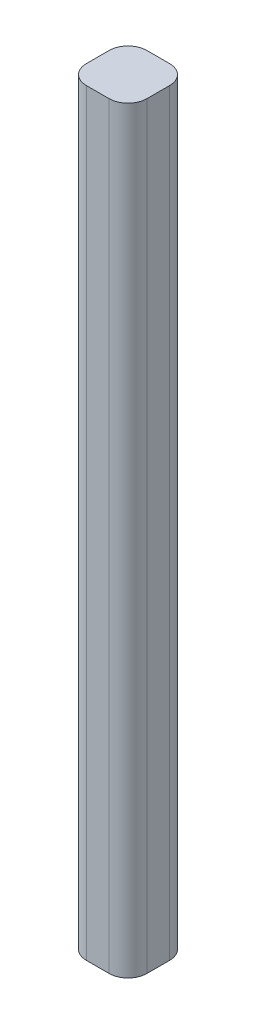
SolidWorks part; units mm, degrees
ref_plane "Front Plane" through (0, 0, 0) normal (0, 0, 1) x (1, 0, 0)
ref_plane "Top Plane" through (0, 0, 0) normal (0, 1, 0) x (1, 0, 0)
ref_plane "Right Plane" through (0, 0, 0) normal (1, 0, 0) x (0, 0, -1)
sketch "Sketch1" plane through (0, 0, 0) normal (0, 1, 0) x (1, 0, 0)
  line L1 (15, -40) -> (-15, -40)
  line L2 (40, -15) -> (40, 15)
  line L3 (15, 40) -> (-15, 40)
  line L4 (-40, -15) -> (-40, 15)
  line L5 (40, -40) -> (-40, 40) construction
  line L6 (40, 40) -> (-40, -40) construction
  circle A0 centre (0, 0) radius 38.75 construction
  arc A1 (-15, -40) -> (-40, -15) centre (-15, -15) cw
  arc A2 (40, 15) -> (15, 40) centre (15, 15) ccw
  arc A3 (15, -40) -> (40, -15) centre (15, -15) ccw
  arc A4 (-15, 40) -> (-40, 15) centre (-15, 15) ccw
  dimension "D1" = 77.5
  dimension "D4" = 25
  dimension "D2" = 80
  dimension "D3" = 80
extrude "Boss-Extrude1" add sketch "Sketch1" along normal mid plane 1000
